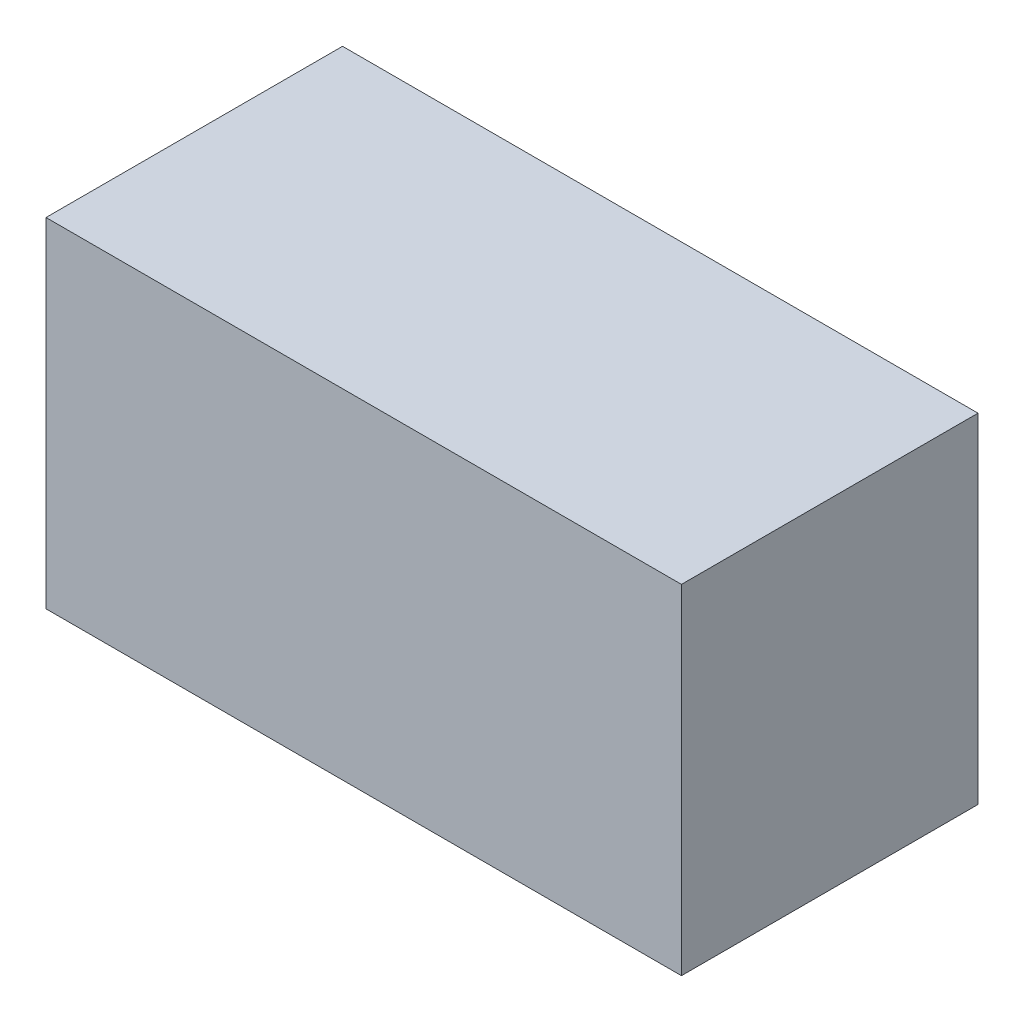
SolidWorks part; units mm, degrees
ref_plane "Front Plane" through (0, 0, 0) normal (0, 0, 1) x (1, 0, 0)
ref_plane "Top Plane" through (0, 0, 0) normal (0, 1, 0) x (1, 0, 0)
ref_plane "Right Plane" through (0, 0, 0) normal (1, 0, 0) x (0, 0, -1)
sketch "Sketch1" plane through (0, 0, 0) normal (0, 0, 1) x (1, 0, 0)
  line L13 (130.9044, -53.5586) -> (175.9044, -53.5586)
  line L14 (130.9044, -53.5586) -> (130.9044, -77.5586)
  line L15 (130.9044, -77.5586) -> (175.9044, -77.5586)
  line L16 (175.9044, -53.5586) -> (175.9044, -77.5586)
  point P4 (0, 0)
  point P5 (0, 0)
extrude "Boss-Extrude2" add sketch "Sketch1" along normal blind 21 contours L14 L13 L16 L15
